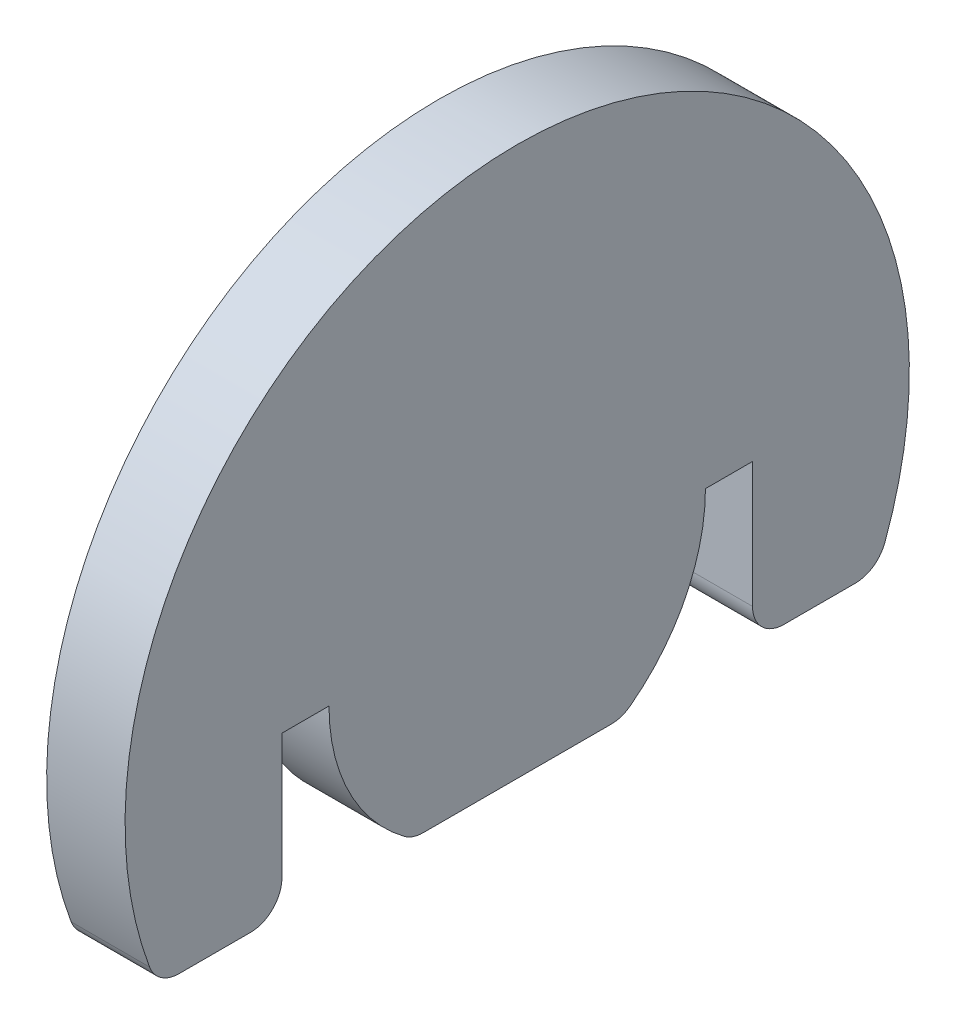
SolidWorks part; units mm, degrees
material "Mahogany"
ref_plane "Front Plane" through (0, 0, 0) normal (0, 0, 1) x (1, 0, 0)
ref_plane "Top Plane" through (0, 0, 0) normal (0, 1, 0) x (1, 0, 0)
ref_plane "Right Plane" through (0, 0, 0) normal (1, 0, 0) x (0, 0, -1)
sketch "Sketch1" plane through (0, 0, 0) normal (1, 0, 0) x (0, 0, -1)
  line L0 (-7.5, -5) -> (-11.4564, -5)
  line L1 (-3.3166, -5) -> (-4.1533, -5)
  line L2 (-4.1533, -5) -> (3.3166, -5)
  line L3 (7.5, -5) -> (11.4564, -5)
  line L4 (-6, 0) -> (-7.5, 0)
  line L5 (6, 0) -> (7.5, 0)
  line L6 (-7.5, 0) -> (-7.5, -5)
  line L7 (0, 2.5735) -> (0, -2.5735) construction
  line L8 (7.5, 0) -> (7.5, -5)
  line L9 (-11.4564, 5) -> (11.4564, 5)
  arc A0 (-5.5902, -5) -> (7.5, 0) centre (0, 0) ccw construction
  circle A1 centre (0, 0) radius 12.5
  arc A2 (-6, 0) -> (6, 0) centre (0, 0) ccw construction
  arc A4 (-11.4564, -5) -> (11.4564, -5) centre (0, 0) cw construction
  arc A6 (-3.3166, -5) -> (-6, 0) centre (0, 0) cw
  circle A8 centre (0, 0) radius 6 construction
  arc A9 (6, 0) -> (3.3166, -5) centre (0, 0) cw
  arc A10 (7.5, 0) -> (5.5902, -5) centre (0, 0) cw construction
  circle A11 centre (0, 0) radius 7.5 construction
  arc A12 (-11.4564, -5) -> (-11.4564, 5) centre (0, 0) cw
  arc A13 (11.4564, -5) -> (11.4564, 5) centre (0, 0) ccw
  dimension "D4" = 15
  dimension "D5" = 5
  dimension "D3" = 5
  dimension "D1" = 5
  dimension "D2" = 1.5
extrude "Boss-Extrude1" add sketch "Sketch1" along normal mid plane 2.5 contours L3 A13 L9 A12 L0 L6 L4 A6 L1 L2 A9 L5 L8 | L9 A1
fillet "Fillet1" radius 1 6 edges at (0, -5, -3.3166) (0, -5, 3.3166) (0, -5, 7.5) (0, -5, -11.4564) (0, -5, -7.5) (0, -5, 11.4564)
